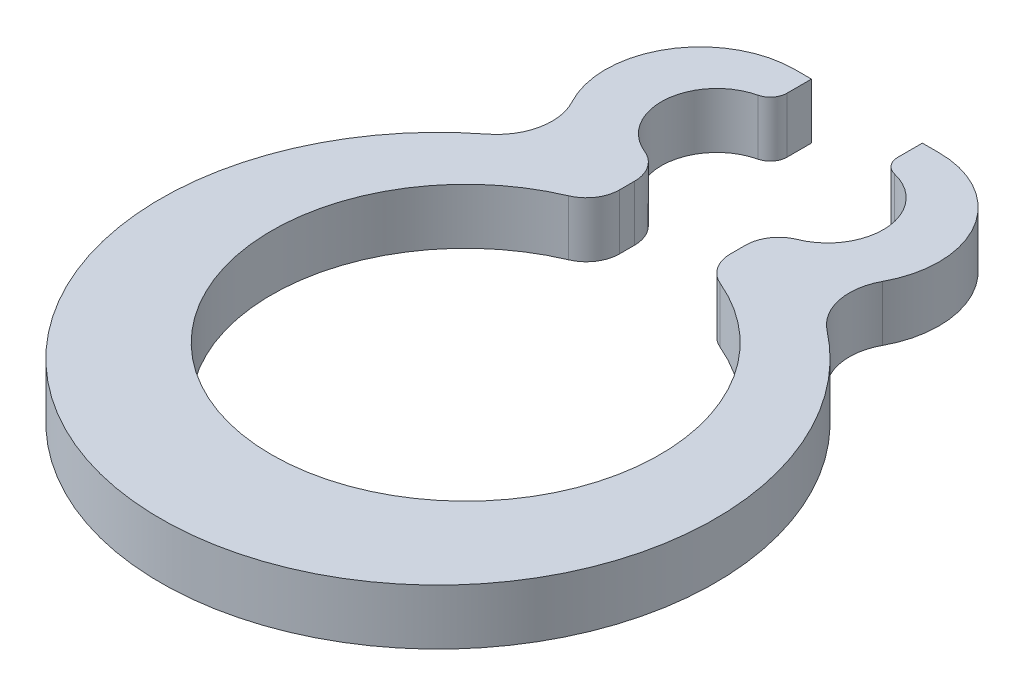
SolidWorks part; units mm, degrees
ref_plane "Спереди" through (0, 0, 0) normal (0, 0, 1) x (1, 0, 0)
ref_plane "Сверху" through (0, 0, 0) normal (0, 1, 0) x (1, 0, 0)
ref_plane "Справа" through (0, 0, 0) normal (1, 0, 0) x (0, 0, -1)
sketch "Эскиз1" plane through (0, 0, 0) normal (0, 1, 0) x (1, 0, 0)
  line L1 (-0.5, 3.3965) -> (-0.5, 3.6173)
  line L6 (0.5, 3.6173) -> (0.65, 3.6173)
  line L7 (-0.65, 3.6173) -> (-0.5, 3.6173)
  line L9 (0.5, 3.3965) -> (0.5, 3.6173)
  line L11 (0.5, 1.8875) -> (0.5, 2.0225)
  line L13 (-0.5, 1.8875) -> (-0.5, 2.0225)
  arc A0 (-0.6829, 1.6112) -> (0.6829, 1.6112) centre (0, 0) ccw
  arc A2 (-1.5332, 1.7247) -> (1.5332, 1.7247) centre (0, -0.25) ccw
  arc A5 (-0.6154, 3.2506) -> (-0.6875, 2.3006) centre (-0.5, 2.7641) ccw
  arc A6 (0.6875, 2.3006) -> (0.6154, 3.2506) centre (0.5, 2.7641) ccw
  arc A7 (-0.65, 3.6173) -> (-1.4002, 2.3577) centre (-0.65, 2.7641) ccw
  arc A8 (1.4002, 2.3577) -> (0.65, 3.6173) centre (0.65, 2.7641) ccw
  arc A9 (1.4002, 2.3577) -> (1.5332, 1.7247) centre (1.8399, 2.1196) ccw
  arc A10 (-1.4002, 2.3577) -> (-1.5332, 1.7247) centre (-1.8399, 2.1196) cw
  arc A11 (0.5, 2.0225) -> (0.6875, 2.3006) centre (0.8, 2.0225) cw
  arc A12 (0.5, 1.8875) -> (0.6829, 1.6112) centre (0.8, 1.8875) ccw
  arc A13 (-0.5, 1.8875) -> (-0.6829, 1.6112) centre (-0.8, 1.8875) cw
  arc A14 (-0.5, 2.0225) -> (-0.6875, 2.3006) centre (-0.8, 2.0225) ccw
  arc A15 (0.5, 3.3965) -> (0.6154, 3.2506) centre (0.65, 3.3965) ccw
  arc A16 (-0.5, 3.3965) -> (-0.6154, 3.2506) centre (-0.65, 3.3965) cw
  dimension "D1" = 3.5
  dimension "D2" = 5
  dimension "D4" = 0.5
  dimension "D5" = 1
  dimension "D7" = 1.3
  dimension "D6" = 0.5
  dimension "D8" = 0.3
  dimension "D9" = 0.15
  dimension "D3" = 0.25
extrude "Бобышка-Вытянуть1" add sketch "Эскиз1" along normal blind 0.5
